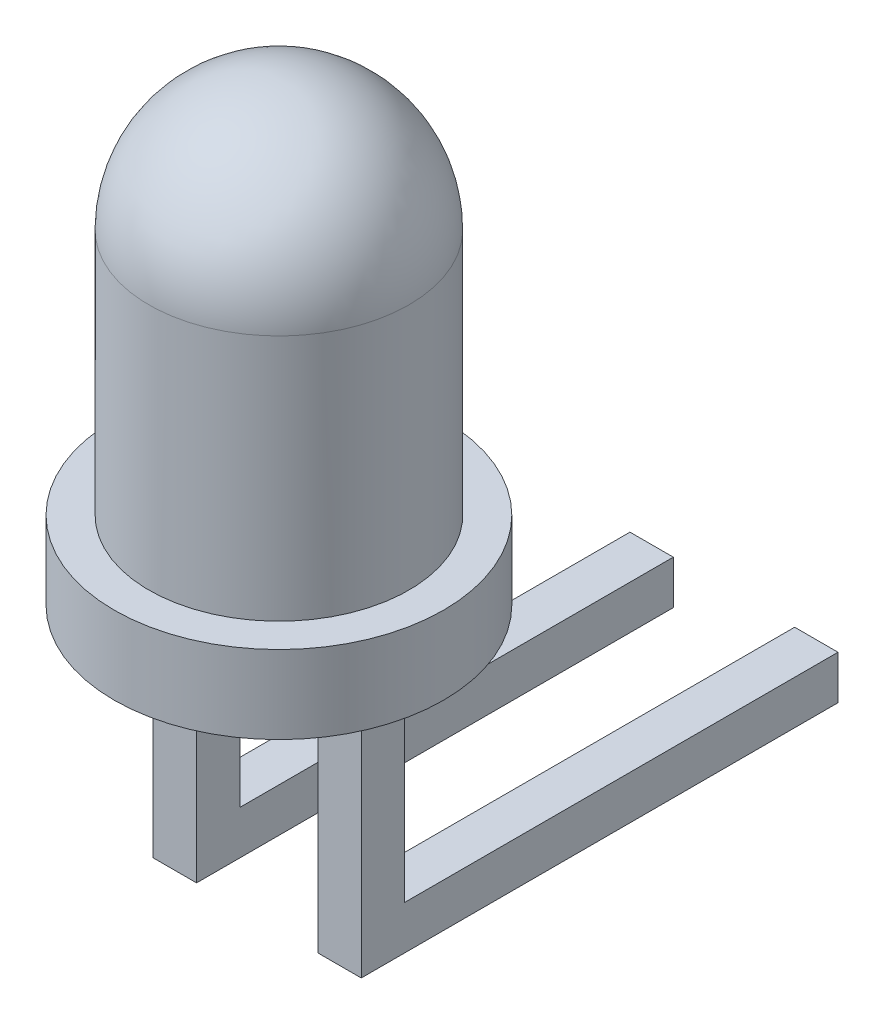
SolidWorks part; units mm, degrees
ref_plane "Přední rovina" through (0, 0, 0) normal (0, 0, 1) x (1, 0, 0)
ref_plane "Horní rovina" through (0, 0, 0) normal (0, 1, 0) x (1, 0, 0)
ref_plane "Pravá rovina" through (0, 0, 0) normal (1, 0, 0) x (0, 0, -1)
sketch "Skica1" plane through (0, 0, 0) normal (0, 0, 1) x (1, 0, 0)
  line L0 (-1.5, 6.0665) -> (-1.5, 3.2165)
  line L1 (-1.9, 2.3165) -> (0, 2.3165)
  line L2 (0, 7.5665) -> (0, 2.3165)
  line L3 (-1.5, 3.2165) -> (-1.9, 3.2165)
  line L4 (-1.9, 3.2165) -> (-1.9, 2.3165)
  line L5 (0, 7.5665) -> (0, 2.3165) construction
  arc A0 (0, 7.5665) -> (-1.5, 6.0665) centre (0, 6.0665) ccw
  dimension "D1" = 0.9
  dimension "D2" = 5.25
  dimension "D3" = 3.8
  dimension "D4" = 2.85
revolve "Rotovat1" add sketch "Skica1" angle 360 about L5
sketch "Skica2" plane through (0, 0, 0) normal (0, 0, 1) x (1, 0, 0)
  line L0 (0.7, 2.3165) -> (1.2, 2.3165)
  line L1 (-1.9, 2.3165) -> (1.9, 2.3165) construction
  line L2 (1.2, 2.3165) -> (1.2, -0.6835)
  line L3 (-0.7, -0.6835) -> (-1.2, -0.6835)
  line L4 (1.2, -0.6835) -> (0.7, -0.6835)
  line L6 (0.7, -0.6835) -> (0.7, 2.3165)
  line L7 (-0.7, 2.3165) -> (-0.7, -0.6835)
  line L11 (-1.2, -0.6835) -> (-1.2, 2.3165)
  line L12 (-0.7, 2.3165) -> (-1.2, 2.3165)
  dimension "D1" = 0.5
  dimension "D2" = 3
  dimension "D3" = 0.7
  dimension "D4" = 0.7
  dimension "D5" = 0.5
  dimension "D7" = 3
extrude "Přidat vysunutím1" add sketch "Skica2" along normal mid plane 0.5
sketch "Skica3" plane through (0, 0, -0.25) normal (0, 0, -1) x (-1, 0, 0)
  line L0 (0.7, -0.6835) -> (0.7, 2.3165) construction
  line L1 (1.2, -0.6835) -> (0.7, -0.6835)
  line L2 (1.2, -0.6835) -> (1.2, -0.1787)
  line L3 (1.2, -0.1787) -> (0.7, -0.1787)
  line L4 (0.7, -0.6835) -> (0.7, -0.1787)
  line L5 (-1.2, -0.6835) -> (-1.2, 2.3165) construction
  line L6 (-0.7, -0.6835) -> (-1.2, -0.6835)
  line L7 (-0.7, -0.6835) -> (-0.7, -0.1787)
  line L8 (-0.7, -0.1787) -> (-1.2, -0.1787)
  line L9 (-1.2, -0.6835) -> (-1.2, -0.1787)
  dimension "D1" = 0.5048
  dimension "D2" = 0.5048
extrude "Přidat vysunutím2" add sketch "Skica3" along normal blind 5
